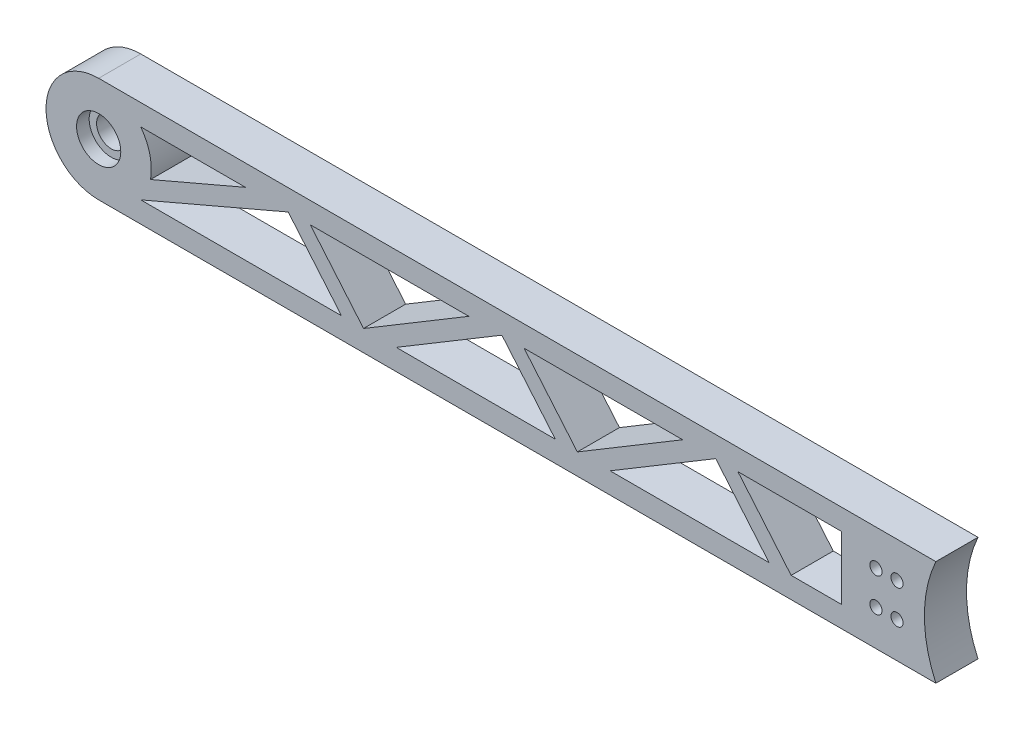
SolidWorks part; units mm, degrees
material "ABS"
ref_plane "前视基准面" through (0, 0, 0) normal (0, 0, 1) x (1, 0, 0)
ref_plane "上视基准面" through (0, 0, 0) normal (0, 1, 0) x (1, 0, 0)
ref_plane "右视基准面" through (0, 0, 0) normal (1, 0, 0) x (0, 0, -1)
other "Configuration Table"
sketch "草图1" plane through (0, 0, 0) normal (0, 0, 1) x (1, 0, 0)
  line L0 (0, 0) -> (223, 0) construction
  line L1 (0, 12.5) -> (199.0678, 12.5)
  line L2 (0, -12.5) -> (199.0678, -12.5)
  arc A0 (0, 12.5) -> (0, -12.5) centre (0, 0) ccw
  arc A1 (199.0678, -12.5) -> (199.0678, 12.5) centre (223, 0) ccw
  dimension "D1" = 12.5
  dimension "D2" = 27
  dimension "D3" = 223
extrude "凸台-拉伸1" add sketch "草图1" along normal blind 10
sketch "草图3" plane through (0, 0, 10) normal (0, 0, 1) x (1, 0, 0)
  line L0 (176.3768, 7.5) -> (176.3768, -7.5)
  line L1 (10, 7.5) -> (196.3768, 7.5)
  line L2 (10, -7.5) -> (198.0625, -7.5)
  line L3 (199.0678, 12.5) -> (0, 12.5) construction
  line L4 (0, -12.5) -> (199.0678, -12.5) construction
  line L5 (10, -7.5) -> (45, 7.5)
  line L6 (34.8456, 7.5) -> (12.3125, -2.1571)
  line L7 (45, 7.5) -> (57.6414, -7.5)
  line L8 (50.231, 7.5) -> (62.8724, -7.5)
  line L9 (62.8724, -7.5) -> (87.8724, 7.5)
  line L10 (70.647, -7.5) -> (95.647, 7.5)
  line L11 (113.6246, -7.5) -> (138.6246, 7.5)
  line L12 (95.7522, 7.5) -> (108.3936, -7.5)
  line L13 (100.9832, 7.5) -> (113.6246, -7.5)
  line L14 (121.3992, -7.5) -> (146.3992, 7.5)
  line L16 (146.5044, 7.5) -> (159.1458, -7.5)
  line L17 (151.7355, 7.5) -> (164.3768, -7.5)
  line L19 (164.3768, -7.5) -> (189.3768, 7.5) [skipped]
  line L20 (172.1514, -7.5) -> (197.1514, 7.5) [skipped]
  circle A0 centre (0, 0) radius 12.5
  circle A1 centre (222.9812, 2.895) radius 27
  point P5 (10, 7.5)
  dimension "D2" = 25
  dimension "D3" = 54
  dimension "D1" = 223
  dimension "D4" = 5
  dimension "D5" = 5
  dimension "D6" = 4
  dimension "D7" = 4
  dimension "D8" = 4
  dimension "D9" = 3
  dimension "D10" = 12
  dimension "D11" = 20
  dimension "D12" = 106.924
  dimension "D13" = 35
  dimension "D14" = 25
extrude "切除-拉伸1" cut sketch "草图3" against normal through all and the other way through all
sketch "草图7" plane through (0, 0, 0) normal (0, 0, -1) x (-1, 0, 0)
  circle A0 centre (0, 0) radius 3.5
  dimension "D1" = 7
extrude "切除-拉伸5" cut sketch "草图7" against normal through all
sketch "草图8" plane through (0, 0, 0) normal (0, 0, -1) x (-1, 0, 0)
  line L0 (0, 0) -> (-223, 0) construction
  circle A0 centre (-223, 0) radius 5
  dimension "D1" = 10
extrude "切除-拉伸6" cut sketch "草图8" against normal blind 3
sketch "草图9" plane through (0, 0, 0) normal (0, 0, -1) x (-1, 0, 0)
  line L0 (0, 0) -> (-223, 0)
  circle A0 centre (-223, 0) radius 3
  dimension "D1" = 6
  dimension "D2" = 223
extrude "切除-拉伸7" cut sketch "草图9" against normal through all
sketch "草图10" plane through (0, 0, 10) normal (0, 0, 1) x (1, 0, 0)
  circle A0 centre (0, 0) radius 5.25
  dimension "D1" = 10.5
extrude "切除-拉伸8" cut sketch "草图10" against normal blind 3
sketch "草图11" plane through (0, 0, 10) normal (0, 0, 1) x (1, 0, 0)
  circle A0 centre (223, 0) radius 27
extrude "切除-拉伸9" cut sketch "草图11" against normal blind 10
sketch "草图12" plane through (0, 0, 10) normal (0, 0, 1) x (1, 0, 0)
  line L0 (0, 0) -> (226, 0) construction
  circle A1 centre (226, 0) radius 30
  dimension "D1" = 226
extrude "切除-拉伸10" cut sketch "草图12" against normal blind 10
sketch "草图13" plane through (0, 0, 10) normal (0, 0, 1) x (1, 0, 0)
  line L0 (0, 0) -> (226, 0) construction
  circle A0 centre (226, 0) radius 30
  point P4 (196, 0)
  point P5 (175.9339, 0)
  dimension "D1" = 226
sketch "草图14" plane through (0, 0, 10) normal (0, 0, 1) x (1, 0, 0)
  line L0 (196, -12.5) -> (196, 12.5) construction
  line L1 (0, -12.5) -> (198.7282, -12.5) construction
  line L2 (198.7282, 12.5) -> (0, 12.5) construction
  line L3 (196, 12.5) -> (181, 12.5)
  line L4 (196, 12.5) -> (193, 12.5)
  line L5 (193, 12.5) -> (193, -12.5)
  line L6 (181, 12.5) -> (181, -12.5)
  line L7 (181, -4) -> (193, -4) construction
  line L8 (184.5, 12.5) -> (184.5, -12.5) construction
  line L9 (189.5, 12.5) -> (189.5, -12.5) construction
  line L10 (181, 4) -> (193, 4) construction
  circle A0 centre (226, 0) radius 30 construction
  circle A7 centre (189.5, -4) radius 1.45
  circle A8 centre (184.5, -4) radius 1.45
  circle A9 centre (184.5, 4) radius 1.45
  circle A10 centre (189.5, 4) radius 1.45
  dimension "D6" = 8.5
  dimension "D7" = 2.9
  dimension "D1" = 15
  dimension "D2" = 3.5
  dimension "D3" = 3
  dimension "D4" = 3.5
  dimension "D5" = 8.5
extrude "切除-拉伸12" cut sketch "草图14" against normal blind 300 contours A9 | A10 | A7 | A8
